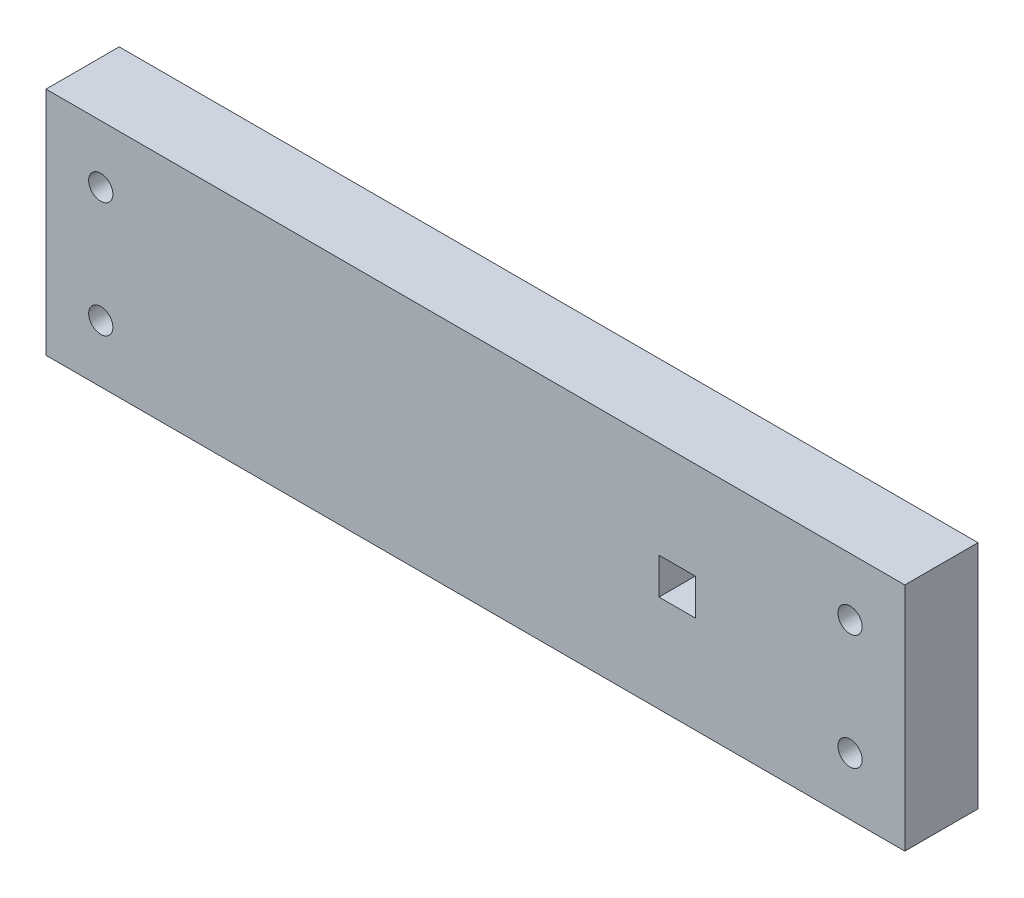
SolidWorks part; units mm, degrees
material "6061-T6 (SS)"
ref_plane "Front Plane" through (0, 0, 0) normal (0, 0, 1) x (1, 0, 0)
ref_plane "Top Plane" through (0, 0, 0) normal (0, 1, 0) x (1, 0, 0)
ref_plane "Right Plane" through (0, 0, 0) normal (1, 0, 0) x (0, 0, -1)
sketch "Sketch1" plane through (0, 0, 0) normal (0, 0, 1) x (1, 0, 0)
  line L0 (-65, 30) -> (-65, 10) construction
  line L1 (-74.5, 40) -> (74.5, 40)
  line L2 (-74.5, 40) -> (-74.5, 0)
  line L3 (-74.5, 0) -> (74.5, 0)
  line L4 (74.5, 40) -> (74.5, 0)
  line L5 (31.85, 23.15) -> (38.15, 23.15)
  line L6 (31.85, 23.15) -> (31.85, 16.85)
  line L7 (31.85, 16.85) -> (38.15, 16.85)
  line L8 (38.15, 23.15) -> (38.15, 16.85)
  line L9 (32, 23) -> (38, 23) construction
  line L10 (32, 23) -> (32, 17) construction
  line L11 (32, 17) -> (38, 17) construction
  line L12 (38, 23) -> (38, 17) construction
  line L13 (0, 0) -> (0, 40) construction
  circle A0 centre (-65, 30) radius 2.5 construction
  circle A1 centre (-65, 10) radius 2.5 construction
  circle A2 centre (65, 10) radius 2.5 construction
  circle A3 centre (65, 30) radius 2.5 construction
  point P10 (0, 0)
  point P14 (35, 23)
  point P15 (35, 23.15)
  point P16 (32, 20)
  point P17 (31.85, 20)
  dimension "D8" = 5
  dimension "D1" = 6.3
  dimension "D2" = 149
  dimension "D3" = 40
  dimension "D4" = 16.85
  dimension "D5" = 32
  dimension "D6" = 6
  dimension "D7" = 20
  dimension "D9" = 10
  dimension "D10" = 65
extrude "Boss-Extrude1" add sketch "Sketch1" along normal blind 12.7 contours L1 L4 L3 L2
sketch "Sketch2" plane through (0, 40, 0) normal (0, 1, 0) x (1, 0, 0)
  line L0 (74.5, -12.7) -> (-74.5, -12.7) construction
  line L1 (37.5, -12.7) -> (31.5, -12.7) construction
  line L2 (37.5, -12.7) -> (37.5, 0) construction
  line L3 (37.5, 0) -> (31.5, 0) construction
  line L4 (31.5, -12.7) -> (31.5, 0) construction
  line L5 (74.5, 0) -> (-74.5, 0) construction
  line L7 (0, 0) -> (0, -12.7) construction
  circle A0 centre (34.5, -6.35) radius 2.5 construction
  point P12 (34.5, 0)
  point P14 (31.5, -6.35)
  dimension "D3" = 5
  dimension "D1" = 31.5
  dimension "D2" = 6
hole_wizard "Tap Drill for M4x0.7 Tap1" positions "3DSketch1" profile "Sketch3" hole size "M4x0.7" standard "ANSI Metric"
sketch3d "3DSketch1"
  point P0 (34.5, 40, 6.35)
sketch "Sketch3" plane through (34.5, 40, 6.35) normal (1, 0, 0) x (0, 0, 1)
  line L0 (0, 0) -> (0, 16.85)
  line L1 (0, 16.85) -> (1.65, 16.85)
  line L2 (1.65, 16.85) -> (1.65, 0)
  line L5 (1.65, 0) -> (0, 0)
  line L11 (0, -6.35) -> (0, 107.95) construction
  dimension "Thru Hole Dia." = 3.3
  dimension "Thru Hole Depth" = 16.85
sketch "Sketch4" plane through (0, 0, 0) normal (0, -1, 0) x (1, 0, 0)
  line L0 (-60, 6.35) -> (60, 6.35) construction
  line L2 (-74.5, 12.7) -> (74.5, 12.7)
  line L3 (-74.5, 12.7) -> (-74.5, 0)
  line L4 (-74.5, 0) -> (74.5, 0)
  line L5 (74.5, 12.7) -> (74.5, 0)
  circle A0 centre (0, 6.35) radius 2.5 construction
  circle A1 centre (60, 6.35) radius 2.5 construction
  circle A2 centre (-60, 6.35) radius 2.5 construction
  point P6 (0, 6.35)
  point P14 (74.5, 6.35)
  dimension "D1" = 5
  dimension "D2" = 120
hole_wizard "Tap Drill for M5x0.8 Tap2" positions "3DSketch2" profile "Sketch5" hole size "M5x0.8" standard "ANSI Metric"
sketch3d "3DSketch2"
  point P0 (-60, 0, 6.35)
  point P2 (0, 0, 6.35)
  point P4 (60, 0, 6.35)
sketch "Sketch5" plane through (-60, 0, 6.35) normal (1, 0, 0) x (0, 0, -1)
  line L0 (0, 0) -> (0, 8.2618)
  line L1 (0, 8.2618) -> (2.1, 7)
  line L2 (2.1, 7) -> (2.1, 0)
  line L5 (2.1, 0) -> (0, 0)
  line L10 (0, 8.2618) -> (-2.1, 7) construction
  line L11 (0, -6.35) -> (0, 107.95) construction
  dimension "Hole Dia." = 4.2
  dimension "Hole Depth" = 7
  dimension "Drill Angle" = 118
hole_wizard "Tap Drill for M5x0.8 Tap3" positions "Sketch6" profile "Sketch7" hole size "M5x0.8" standard "ANSI Metric" end condition up to next
sketch "Sketch6" plane through (0, 0, 12.7) normal (0, 0, 1) x (1, 0, 0)
  point P0 (-65, 30)
  point P2 (-65, 10)
  point P4 (65, 10)
  point P6 (65, 30)
sketch "Sketch7" plane through (-65, 30, 12.7) normal (1, 0, 0) x (0, -1, 0)
  line L0 (0, 0) -> (0, 12.7)
  line L1 (0, 12.7) -> (2.1, 12.7)
  line L2 (2.1, 12.7) -> (2.1, 0)
  line L5 (2.1, 0) -> (0, 0)
  line L11 (0, -6.35) -> (0, 107.95) construction
  dimension "Thru Hole Dia." = 4.2
  dimension "Thru Hole Depth" = 12.7
